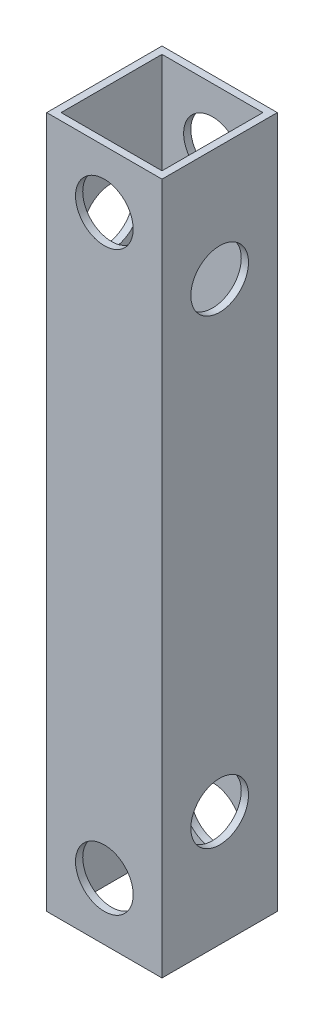
SolidWorks part; units mm, degrees
ref_plane "Front Plane" through (0, 0, 0) normal (0, 0, 1) x (1, 0, 0)
ref_plane "Top Plane" through (0, 0, 0) normal (0, 1, 0) x (1, 0, 0)
ref_plane "Right Plane" through (0, 0, 0) normal (1, 0, 0) x (0, 0, -1)
sketch "Sketch1" plane through (0, 0, 0) normal (0, 1, 0) x (1, 0, 0)
  line L1 (12.7, -12.7) -> (-12.7, -12.7)
  line L2 (12.7, -12.7) -> (12.7, 12.7)
  line L3 (12.7, 12.7) -> (-12.7, 12.7)
  line L4 (-12.7, -12.7) -> (-12.7, 12.7)
  line L5 (12.7, -12.7) -> (-12.7, 12.7) construction
  line L6 (12.7, 12.7) -> (-12.7, -12.7) construction
  line L7 (11.1125, -11.1125) -> (-11.1125, -11.1125)
  line L8 (11.1125, -11.1125) -> (11.1125, 11.1125)
  line L9 (11.1125, 11.1125) -> (-11.1125, 11.1125)
  line L10 (-11.1125, -11.1125) -> (-11.1125, 11.1125)
  line L11 (11.1125, -11.1125) -> (-11.1125, 11.1125) construction
  line L12 (11.1125, 11.1125) -> (-11.1125, -11.1125) construction
  point P0 (0, 0)
  point P6 (0, 0)
  dimension "D1" = 25.4
  dimension "D2" = 25.4
  dimension "D3" = 1.5875
extrude "Boss-Extrude1" add sketch "Sketch1" along normal blind 152.4
sketch "Sketch2" plane through (0, 0, -12.7) normal (0, 0, -1) x (-1, 0, 0)
  line L0 (-12.7, 152.4) -> (12.7, 152.4) construction
  line L1 (12.7, 152.4) -> (12.7, 0) construction
  circle A0 centre (0, 139.7) radius 6.35
  dimension "D1" = 12.7
  dimension "D2" = 12.7
  dimension "D3" = 12.7
extrude "Cut-Extrude1" cut sketch "Sketch2" against normal blind 127
sketch "Sketch3" plane through (12.7, 0, 0) normal (1, 0, 0) x (0, 0, -1)
  line L0 (-12.7, 152.4) -> (12.7, 152.4) construction
  line L1 (-12.7, 152.4) -> (-12.7, 0) construction
  circle A0 centre (0, 127) radius 6.35
  dimension "D1" = 12.7
  dimension "D2" = 25.4
  dimension "D3" = 12.7
extrude "Cut-Extrude2" cut sketch "Sketch3" against normal blind 127
sketch "Sketch4" plane through (0, 0, -12.7) normal (0, 0, -1) x (-1, 0, 0)
  line L0 (-12.7, 152.4) -> (-12.7, 0) construction
  line L1 (-12.7, 0) -> (12.7, 0) construction
  circle A0 centre (0, 12.7) radius 6.35
  dimension "D1" = 12.7
  dimension "D2" = 12.7
  dimension "D3" = 12.7
extrude "Cut-Extrude3" cut sketch "Sketch4" against normal blind 127
sketch "Sketch5" plane through (12.7, 0, 0) normal (1, 0, 0) x (0, 0, -1)
  line L0 (12.7, 152.4) -> (12.7, 0) construction
  line L1 (-12.7, 0) -> (12.7, 0) construction
  circle A0 centre (0, 25.4) radius 6.35
  dimension "D1" = 12.7
  dimension "D2" = 12.7
  dimension "D3" = 25.4
extrude "Cut-Extrude4" cut sketch "Sketch5" against normal blind 127
